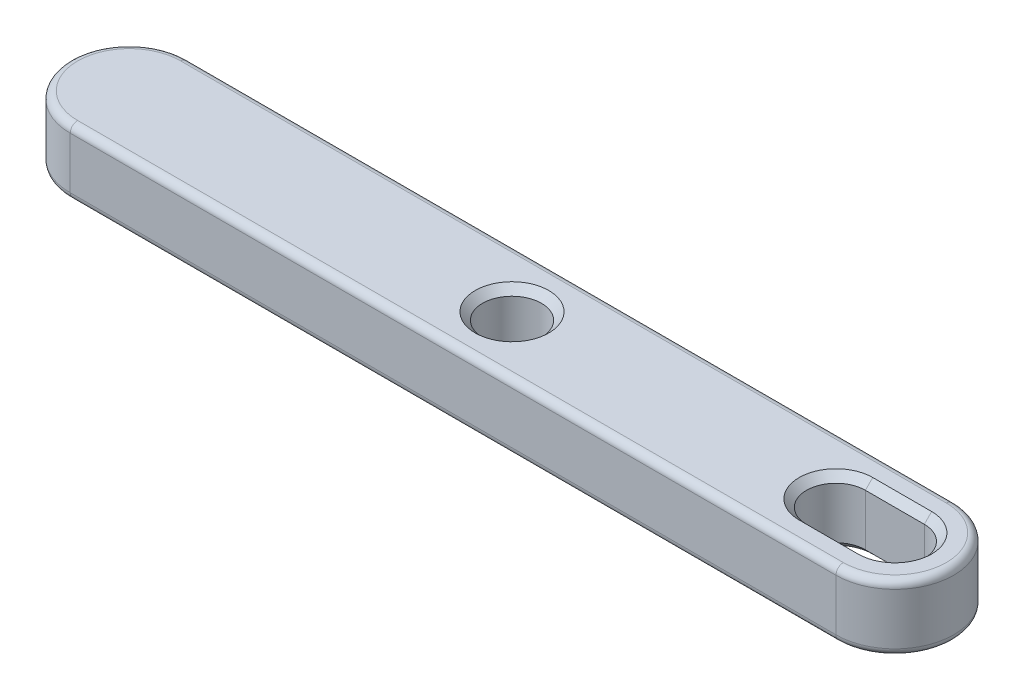
SolidWorks part; units mm, degrees
material "Aço cromo inoxidável"
ref_plane "Plano frontal" through (0, 0, 0) normal (0, 0, 1) x (1, 0, 0)
ref_plane "Plano superior" through (0, 0, 0) normal (0, 1, 0) x (1, 0, 0)
ref_plane "Plano direito" through (0, 0, 0) normal (1, 0, 0) x (0, 0, -1)
sketch "Esboço1" plane through (0, 0, 0) normal (0, 1, 0) x (1, 0, 0)
  line L0 (-26, 0) -> (26, 0) construction
  line L1 (-26, 4) -> (26, 4)
  line L2 (-26, -4) -> (26, -4)
  line L3 (26, 0) -> (22, 0) construction
  line L4 (26, -2) -> (22, -2)
  line L5 (26, 2) -> (22, 2)
  arc A0 (-26, 4) -> (-26, -4) centre (-26, 0) ccw
  arc A1 (26, -4) -> (26, 4) centre (26, 0) ccw
  circle A2 centre (0, 0) radius 2
  arc A3 (26, -2) -> (26, 2) centre (26, 0) ccw
  arc A4 (22, 2) -> (22, -2) centre (22, 0) ccw
  point P2 (0, 0)
  point P12 (24, 0)
  dimension "D3" = 4
  dimension "D1" = 8
  dimension "D2" = 60
  dimension "D4" = 4
  dimension "D5" = 8
extrude "Ressalto-extrusão1" add sketch "Esboço1" along normal mid plane 4.5
chamfer "Chanfro1" distance 0.5 angle 45 10 edges at (28, -2.25, 0) (24, -2.25, -2) (24, -2.25, 2) (20, -2.25, 0) (0, -2.25, 2) (24, 2.25, 2) (28, 2.25, 0) (20, 2.25, 0) (24, 2.25, -2) (0, 2.25, 2)
fillet "Filete1" radius 0.5 8 edges at (-30, 2.25, 0) (0, 2.25, -4) (30, 2.25, 0) (-30, -2.25, 0) (0, -2.25, -4) (30, -2.25, 0) (0, 2.25, 4) (0, -2.25, 4)
